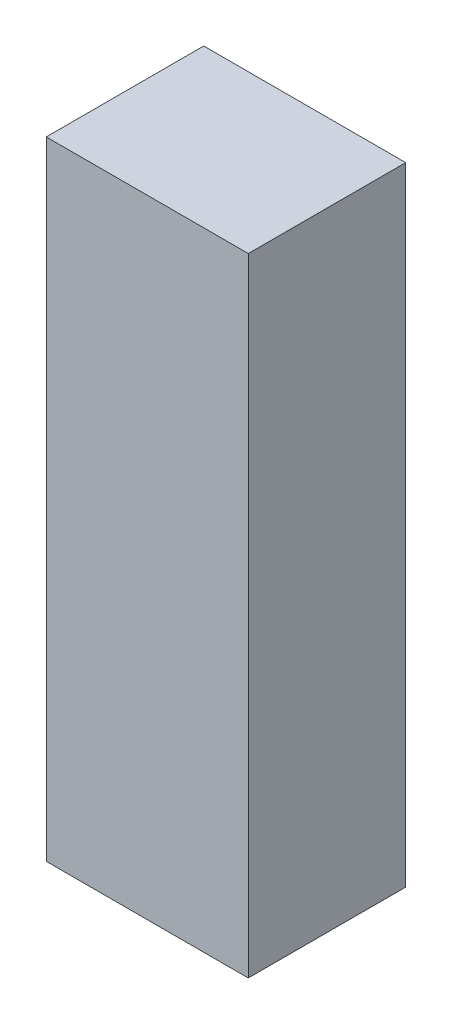
SolidWorks part; units mm, degrees
ref_plane "Plano frontal" through (0, 0, 0) normal (0, 0, 1) x (1, 0, 0)
ref_plane "Plano superior" through (0, 0, 0) normal (0, 1, 0) x (1, 0, 0)
ref_plane "Plano direito" through (0, 0, 0) normal (1, 0, 0) x (0, 0, -1)
other "Centro da massa"
sketch "Esboço1" plane through (0, 0, 0) normal (0, 0, 1) x (1, 0, 0)
  line L1 (17, 52.8) -> (-17, 52.8)
  line L2 (17, 52.8) -> (17, -52.8)
  line L3 (17, -52.8) -> (-17, -52.8)
  line L4 (-17, 52.8) -> (-17, -52.8)
  line L5 (17, 52.8) -> (-17, -52.8) construction
  line L6 (17, -52.8) -> (-17, 52.8) construction
  point P0 (0, 0)
  dimension "D1" = 105.6
  dimension "D2" = 34
extrude "Ressalto-extrusão1" add sketch "Esboço1" along normal blind 26.5
